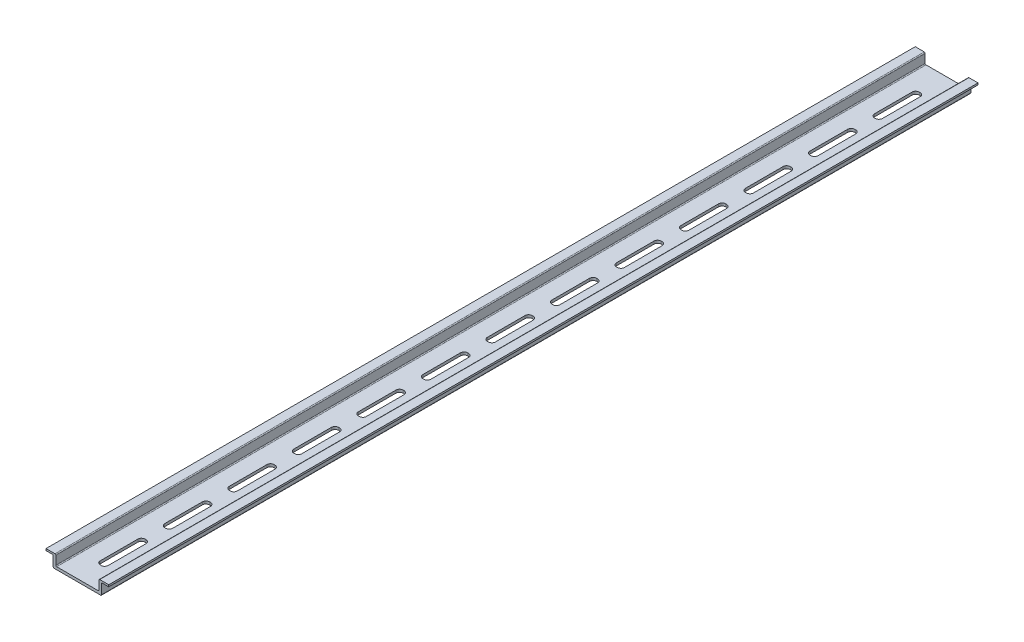
SolidWorks part; units mm, degrees
material "Alloy Steel (SS)"
ref_plane "Front Plane" through (0, 0, 0) normal (0, 0, 1) x (1, 0, 0)
ref_plane "Top Plane" through (0, 0, 0) normal (0, 1, 0) x (1, 0, 0)
ref_plane "Right Plane" through (0, 0, 0) normal (1, 0, 0) x (0, 0, -1)
sketch "Sketch1" plane through (0, 0, 0) normal (0, 0, 1) x (1, 0, 0)
  line L0 (-13.5, 0) -> (13.5, 0)
  line L1 (13.5, 0) -> (13.5, 6.3)
  line L2 (13.5, 6.3) -> (17.5, 6.3)
  line L3 (17.5, 6.3) -> (17.5, 7.3)
  line L4 (17.5, 7.3) -> (12, 7.3)
  line L5 (12, 7.3) -> (12, 1.5)
  line L6 (12, 1.5) -> (-12, 1.5)
  line L7 (-12, 1.5) -> (-12, 7.3)
  line L8 (-12, 7.3) -> (-17.5, 7.3)
  line L9 (-17.5, 7.3) -> (-17.5, 6.3)
  line L10 (-17.5, 6.3) -> (-13.5, 6.3)
  line L11 (-13.5, 6.3) -> (-13.5, 0)
  point P10 (0, 1.5)
  dimension "D1" = 7.3
  dimension "D2" = 1
  dimension "D3" = 27
  dimension "D4" = 35
  dimension "D5" = 24
  dimension "D6" = 1.5
extrude "Boss-Extrude1" add sketch "Sketch1" along normal mid plane 485
fillet "Fillet1" radius 0.5 8 edges at (13.5, 0, 0) (-13.5, 0, 0) (12, 1.5, 0) (12, 7.3, 0) (-12, 1.5, 0) (-12, 7.3, 0) (13.5, 6.3, 0) (-13.5, 6.3, 0)
sketch "Sketch2" plane through (0, 1.5, 0) normal (0, 1, 0) x (1, 0, 0)
  line L1 (-2.25, 227.5) -> (2.25, 227.5)
  line L2 (-2.25, 227.5) -> (-2.25, 202.5)
  line L3 (-2.25, 202.5) -> (2.25, 202.5)
  line L4 (2.25, 227.5) -> (2.25, 202.5)
  line L5 (-2.25, 227.5) -> (2.25, 202.5) construction
  line L6 (-2.25, 202.5) -> (2.25, 227.5) construction
  line L7 (11.5, 242.5) -> (-11.5, 242.5) construction
  point P0 (0, 215)
  dimension "D1" = 15
  dimension "D2" = 25
  dimension "D3" = 4.5
extrude "Cut-Extrude1" cut sketch "Sketch2" against normal through all
fillet "Fillet2" radius 2 4 edges at (2.25, 0.75, -227.5) (-2.25, 0.75, -227.5) (2.25, 0.75, -202.5) (-2.25, 0.75, -202.5)
pattern_linear "LPattern1" count 13 spacing 36 along (0, 0, 1) of "Cut-Extrude1", "Fillet2"
